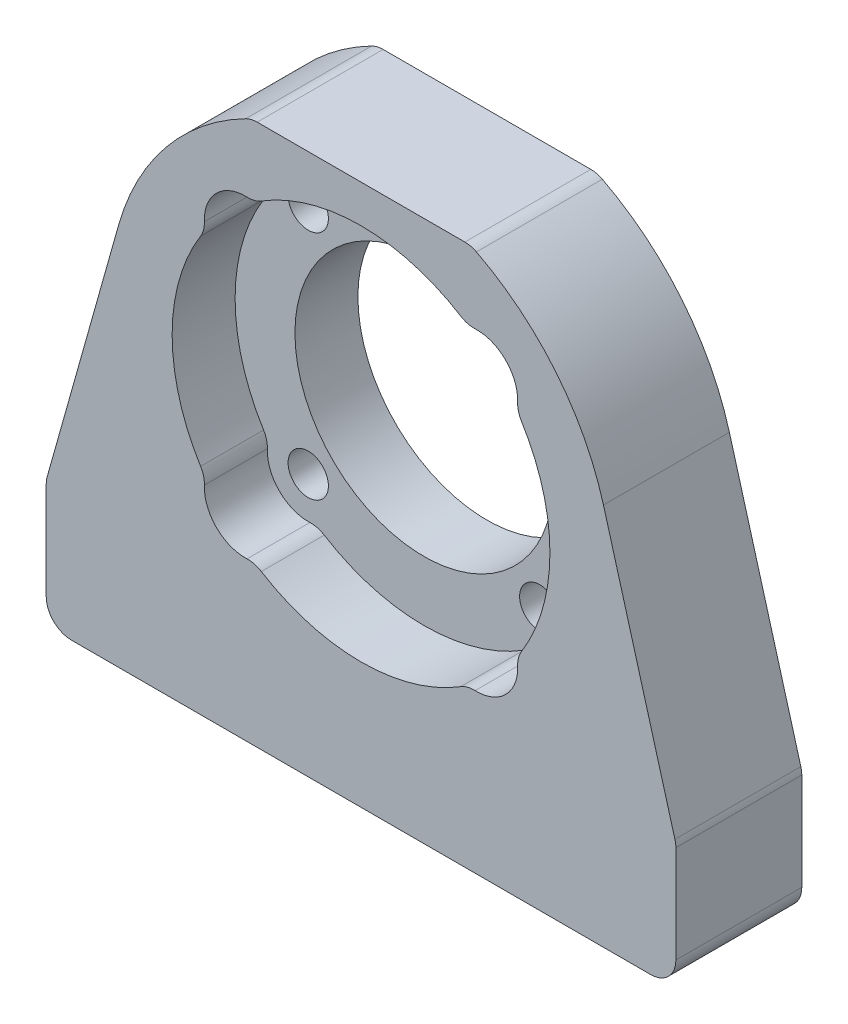
SolidWorks part; units mm, degrees
material "5052-H34"
ref_plane "正面" through (0, 0, 0) normal (0, 0, 1) x (1, 0, 0)
ref_plane "平面" through (0, 0, 0) normal (0, 1, 0) x (1, 0, 0)
ref_plane "右側面" through (0, 0, 0) normal (1, 0, 0) x (0, 0, -1)
sketch "ｽｹｯﾁ1" plane through (0, 0, 0) normal (0, 0, 1) x (1, 0, 0)
  line L0 (0, 0) -> (0, -20) construction
  line L1 (-9.1924, 9.1924) -> (9.1924, 9.1924) construction
  line L2 (-9.1924, 9.1924) -> (-9.1924, -9.1924) construction
  line L3 (-9.1924, -9.1924) -> (9.1924, -9.1924) construction
  line L4 (9.1924, 9.1924) -> (9.1924, -9.1924) construction
  line L5 (-9.1924, 9.1924) -> (9.1924, -9.1924) construction
  line L6 (-9.1924, -9.1924) -> (9.1924, 9.1924) construction
  line L7 (-25, -15) -> (-19.2517, 5.4195)
  line L9 (-25, -15) -> (-25, -25)
  line L10 (-25, -25) -> (25, -25)
  line L11 (25, -15) -> (25, -25)
  line L12 (-25, -15) -> (25, -25) construction
  line L13 (-25, -25) -> (25, -15) construction
  line L14 (25, -15) -> (19.2517, 5.4195)
  line L15 (0, 0) -> (0, 18) construction
  line L16 (-8.7178, 18) -> (8.7178, 18)
  circle A0 centre (0, 0) radius 10.25
  circle A1 centre (9.1924, 9.1924) radius 1.6
  circle A2 centre (9.1924, -9.1924) radius 1.6
  circle A3 centre (-9.1924, -9.1924) radius 1.6
  circle A4 centre (-9.1924, 9.1924) radius 1.6
  arc A5 (19.2517, 5.4195) -> (8.7178, 18) centre (0, 0) ccw
  arc A6 (-8.7178, 18) -> (-19.2517, 5.4195) centre (0, 0) ccw
  point P24 (0, 18)
  dimension "D1" = 20.5
  dimension "D3" = 3.2
  dimension "D5" = 40
  dimension "D2" = 26
  dimension "D6" = 10
  dimension "D7" = 50
  dimension "D8" = 20
  dimension "D9" = 18
  dimension "D4" = 4
extrude "ﾎﾞｽ - 押し出し1" add sketch "ｽｹｯﾁ1" along normal blind 10
sketch "ｽｹｯﾁ3" plane through (0, -25, 0) normal (0, -1, 0) x (1, 0, 0)
  line L0 (0, 0) -> (0, 10) construction
  line L1 (-25, 10) -> (25, 10) construction
  line L2 (0, 5) -> (-20, 5) construction
  circle A0 centre (-20, 5) radius 1.65
  circle A1 centre (20, 5) radius 1.65
  dimension "D1" = 3.3
  dimension "D2" = 40
extrude "ｶｯﾄ - 押し出し2" cut sketch "ｽｹｯﾁ3" against normal blind 10
fillet "ﾌｨﾚｯﾄ1" radius 2 6 edges at (8.7178, 18, 5) (-8.7178, 18, 5) (-25, -15, 5) (-25, -25, 5) (25, -25, 5) (25, -15, 5)
sketch "ｽｹｯﾁ4" plane through (0, 0, 10) normal (0, 0, 1) x (1, 0, 0)
  circle A0 centre (9.1924, 9.1924) radius 1.6 construction
  circle A1 centre (9.1924, 9.1924) radius 1.6
  arc A2 (12.3657, 8.4905) -> (8.4905, 12.3657) centre (9.1924, 9.1924) ccw
  arc A3 (8.4905, -12.3657) -> (12.3657, -8.4905) centre (9.1924, -9.1924) ccw
  arc A4 (-12.3657, -8.4905) -> (-8.4905, -12.3657) centre (-9.1924, -9.1924) ccw
  arc A5 (-8.4905, 12.3657) -> (-12.3657, 8.4905) centre (-9.1924, 9.1924) ccw
  circle A6 centre (9.1924, -9.1924) radius 1.6 construction
  arc A7 (-12.3657, 8.4905) -> (-12.3657, -8.4905) centre (0, 0) ccw
  arc A8 (-8.4905, -12.3657) -> (8.4905, -12.3657) centre (0, 0) ccw
  arc A9 (12.3657, -8.4905) -> (12.3657, 8.4905) centre (0, 0) ccw
  arc A11 (8.4905, 12.3657) -> (-8.4905, 12.3657) centre (0, 0) ccw
  dimension "D1" = 6.5
  dimension "D3" = 30
  dimension "D2" = 4
extrude "ｶｯﾄ - 押し出し3" cut sketch "ｽｹｯﾁ4" against normal blind 5
fillet "ﾌｨﾚｯﾄ2" radius 2 8 edges at (-12.3657, -8.4905, 7.5) (-8.4905, -12.3657, 7.5) (8.4905, -12.3657, 7.5) (12.3657, -8.4905, 7.5) (12.3657, 8.4905, 7.5) (8.4905, 12.3657, 7.5) (-8.4905, 12.3657, 7.5) (-12.3657, 8.4905, 7.5)
